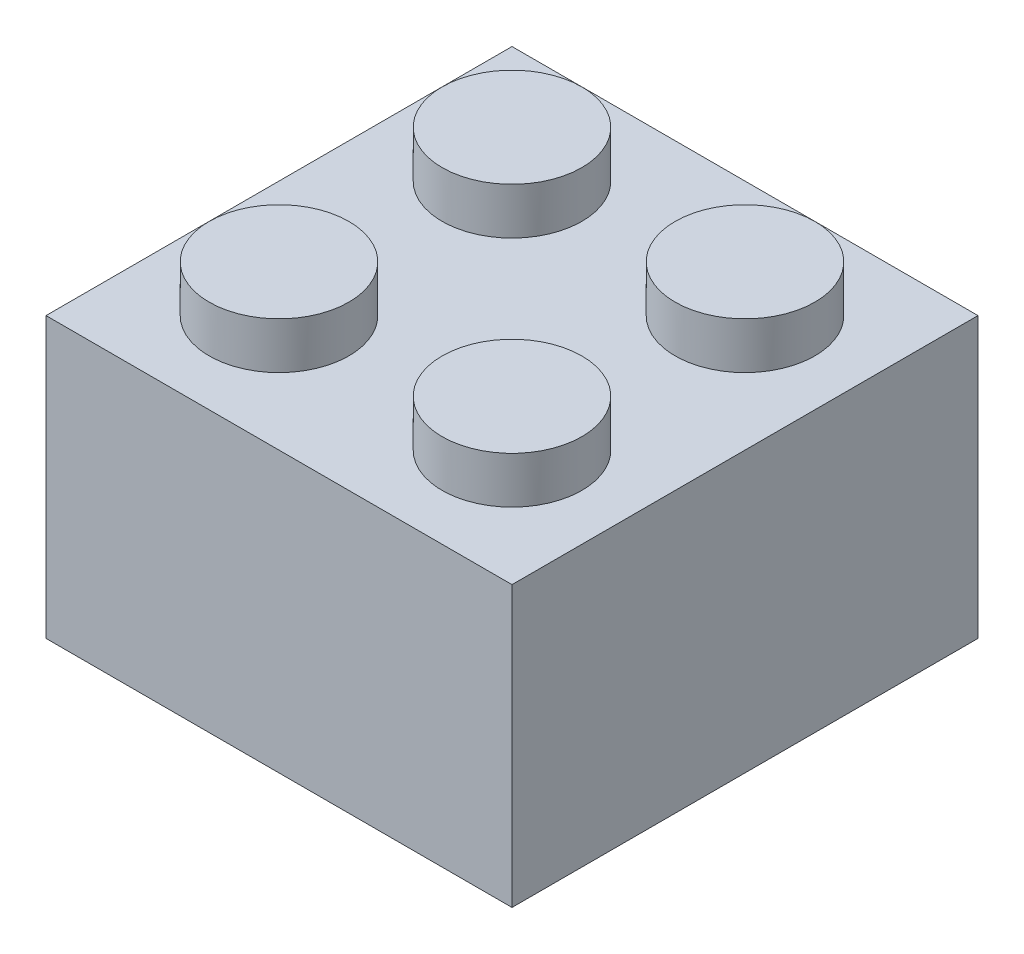
SolidWorks part; units mm, degrees
ref_plane "Front Plane" through (0, 0, 0) normal (0, 0, 1) x (1, 0, 0)
ref_plane "Top Plane" through (0, 0, 0) normal (0, 1, 0) x (1, 0, 0)
ref_plane "Right Plane" through (0, 0, 0) normal (1, 0, 0) x (0, 0, -1)
sketch "Sketch1" plane through (0, 0, 0) normal (0, 1, 0) x (1, 0, 0)
  line L1 (0, 0) -> (16, 0)
  line L2 (0, 0) -> (0, 16)
  line L3 (0, 16) -> (16, 16)
  line L4 (16, 0) -> (16, 16)
  dimension "D1" = 16
  dimension "D2" = 16
extrude "Boss-Extrude1" add sketch "Sketch1" along normal blind 9.6
sketch "Sketch2" plane through (0, 9.6, 0) normal (0, 1, 0) x (1, 0, 0)
  line L0 (8, 0) -> (8, 16) construction
  line L1 (0, 0) -> (16, 0) construction
  line L2 (16, 16) -> (0, 16) construction
  line L3 (16, 0) -> (16, 4) construction
  line L4 (16, 0) -> (16, 16) construction
  line L5 (16, 4) -> (12, 4) construction
  circle A0 centre (12, 4) radius 2.4
  dimension "D3" = 4.8
  dimension "D1" = 4
  dimension "D2" = 4
extrude "Boss-Extrude2" add sketch "Sketch2" along normal blind 1.6
pattern_linear "LPattern1" count 2 spacing 8 along (-1, 0, 0) count 4 spacing 8 along (0, 0, -1) of "Boss-Extrude2"
shell "Shell1" thickness 1.6
